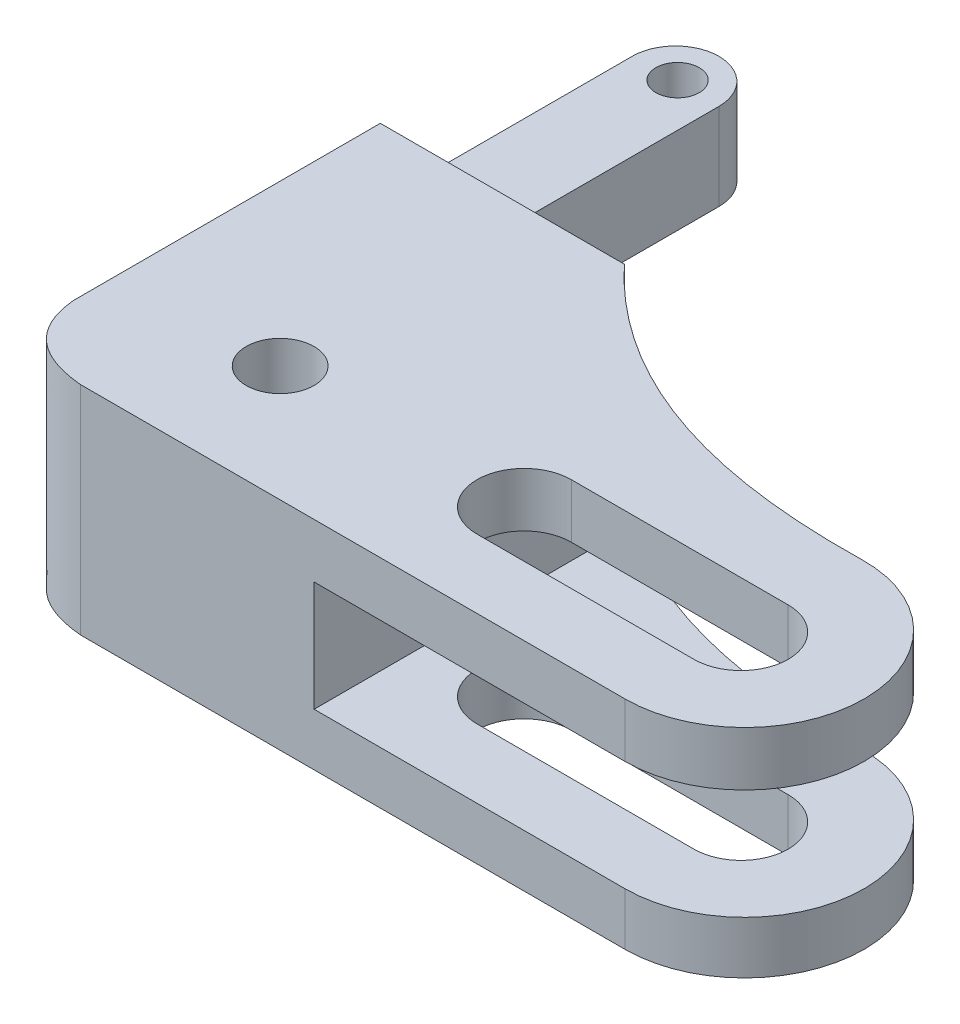
SolidWorks part; units mm, degrees
ref_plane "Front Plane" through (0, 0, 0) normal (0, 0, 1) x (1, 0, 0)
ref_plane "Top Plane" through (0, 0, 0) normal (0, 1, 0) x (1, 0, 0)
ref_plane "Right Plane" through (0, 0, 0) normal (1, 0, 0) x (0, 0, -1)
sketch "Sketch1" plane through (0, 0, 0) normal (0, 1, 0) x (1, 0, 0)
  line L0 (-45, 0) -> (0, 0)
  line L3 (29.5216, -48) -> (69.5216, -48) construction
  line L4 (29.5216, -39.3043) -> (69.5216, -39.3043)
  line L5 (29.5216, -56.6957) -> (69.5216, -56.6957)
  line L6 (-15.4784, -48) -> (-15.4784, 0) construction
  line L7 (-15.4784, -48) -> (29.5216, -48) construction
  line L9 (-45, 0) -> (-45, -50.496)
  line L10 (69.5079, -69.3713) -> (-19.3374, -69.3713)
  line L13 (-45, -56.6957) -> (-45, -50.496)
  line L15 (-30.9188, -69.3713) -> (-19.3374, -69.3713)
  arc A1 (29.5216, -39.3043) -> (29.5216, -56.6957) centre (29.5216, -48) ccw
  arc A2 (69.5216, -56.6957) -> (69.5216, -39.3043) centre (69.5216, -48) ccw
  circle A3 centre (-15.4784, -48) radius 6.25
  arc A4 (69.056, -25.2911) -> (69.5079, -69.3713) centre (69.5079, -47.3289) cw
  spline S0 degree 3 poles (0, 0) (17.366, -18.5561) (40.5073, -25.8765) (69.056, -25.2911) knots 0 0 0 0 1 1 1 1
  spline S1 degree 2 poles (-45, -56.6957) (-43.8988, -68.2331) (-30.9188, -69.3713) knots 0 0 0 1 1 1
  point P11 (49.5216, -48)
  dimension "D3" = 12.5
  dimension "D1" = 40
  dimension "D2" = 45
  dimension "D4" = 45
  dimension "D5" = 48
extrude "Boss-Extrude1" add sketch "Sketch1" along normal blind 40
sketch "Sketch3" plane through (0, 0, 0) normal (0, 0, -1) x (-1, 0, 0)
  line L0 (45, 27.4793) -> (29, 27.4793)
  line L1 (45, 40) -> (45, 0) construction
  line L2 (29, 27.4793) -> (29, 11.4793)
  line L3 (29, 11.4793) -> (45, 11.4793)
  line L4 (45, 11.4793) -> (45, 27.4793)
  dimension "D1" = 16
  dimension "D2" = 16
extrude "Boss-Extrude2" add sketch "Sketch3" along normal blind 55
sketch "Sketch4" plane through (0, 0, 69.3713) normal (0, 0, 1) x (1, 0, 0)
  line L5 (12.1678, 30.0102) -> (91.6554, 30.0102)
  line L6 (12.1678, 30.0102) -> (12.1678, 9.6884)
  line L7 (12.1678, 9.6884) -> (91.6554, 9.6884)
  line L8 (91.6554, 30.0102) -> (91.6554, 9.6884)
extrude "Cut-Extrude1" cut sketch "Sketch4" against normal blind 60.08
sketch "Sketch7" plane through (0, 27.4793, 0) normal (0, 1, 0) x (1, 0, 0)
  line L0 (-37, 55) -> (-37, 40.0299) construction
  line L1 (-45, 55) -> (-29, 55) construction
  line L2 (-45, 46.4389) -> (-45, 55)
  line L3 (-45, 55) -> (-29, 55)
  line L4 (-29, 55) -> (-29, 46.4389)
  arc A2 (-29, 46.4389) -> (-45, 46.4389) centre (-37, 46.4389) ccw
  dimension "D1" = 16
extrude "Cut-Extrude2" cut sketch "Sketch7" against normal blind 60.08
sketch "Sketch8" plane through (0, 27.4793, 0) normal (0, 1, 0) x (1, 0, 0)
  line L0 (-37, 54.4389) -> (-37, 32.4859) construction
  arc A1 (-29, 46.4389) -> (-45, 46.4389) centre (-37, 46.4389) ccw construction
  circle A2 centre (-37, 46.8195) radius 4
  dimension "D1" = 8
extrude "Cut-Extrude3" cut sketch "Sketch8" against normal blind 60.08
sketch "Sketch10" plane through (0, 40, 0) normal (0, 1, 0) x (1, 0, 0)
  text T0 "<i>Ashish Yadav</i>"
